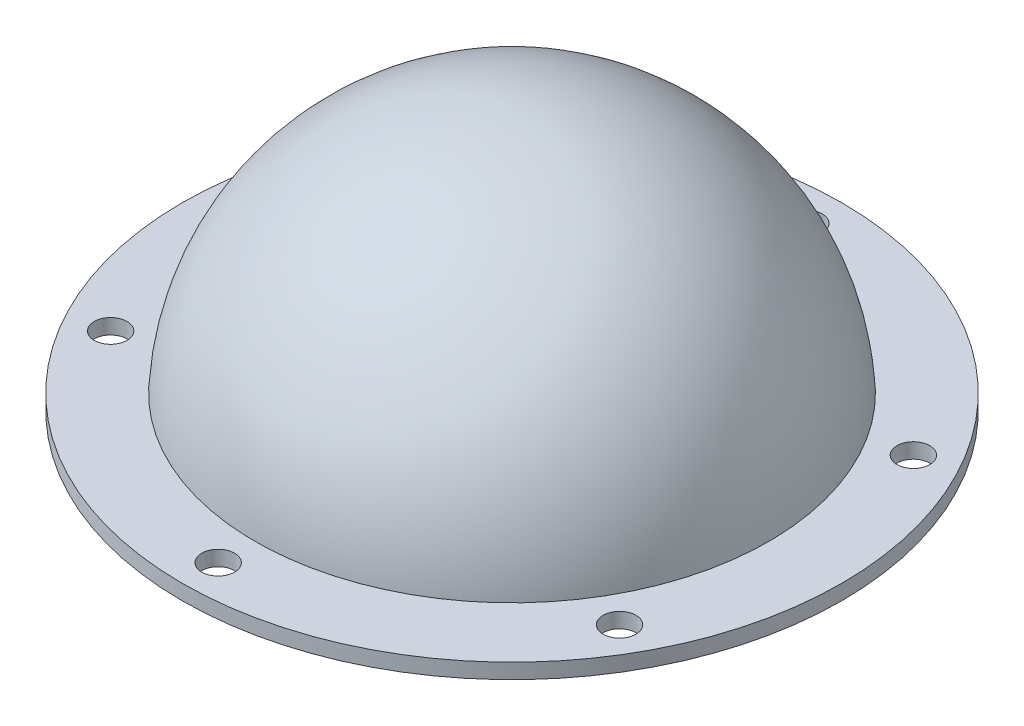
SolidWorks part; units mm, degrees
ref_plane "Front Plane" through (0, 0, 0) normal (0, 0, 1) x (1, 0, 0)
ref_plane "Top Plane" through (0, 0, 0) normal (0, 1, 0) x (1, 0, 0)
ref_plane "Right Plane" through (0, 0, 0) normal (1, 0, 0) x (0, 0, -1)
sketch "Sketch1" plane through (0, 0, 0) normal (1, 0, 0) x (0, 0, -1)
  line L0 (31.75, 0) -> (-31.75, 0) construction
  line L1 (-31.75, 0) -> (-43.201, 0)
  line L2 (-43.201, 0) -> (-43.201, 1.9844)
  line L3 (-43.201, 1.9844) -> (-33.676, 1.9844)
  line L4 (0, -1000) -> (0, 49000) construction
  line L5 (0, 33.7344) -> (0, 31.75)
  arc A0 (-31.75, 0) -> (0, 31.75) centre (0, 0) cw
  arc A1 (-33.676, 1.9844) -> (0, 33.7344) centre (0, 0) cw
  arc A2 (-33.7344, 0) -> (33.7344, 0) centre (0, 0) cw construction
  arc A3 (-31.75, 0) -> (31.75, 0) centre (0, 0) cw construction
  point P4 (0, 0)
  dimension "D1" = 63.5
  dimension "D3" = 9.525
  dimension "D4" = 1.9844
  dimension "D2" = 1.9844
revolve "Revolve1" add sketch "Sketch1" angle 360 about L4
sketch "Sketch2" plane through (0, 1.9844, 0) normal (0, 1, 0) x (1, 0, 0)
  line L0 (0, -38.5) -> (0, 38.5) construction
  line L1 (0, 38.5) -> (-33.342, 19.25) construction
  line L2 (-33.342, 19.25) -> (-33.342, -19.25) construction
  line L3 (-33.342, -19.25) -> (0, -38.5) construction
  line L4 (0, -38.5) -> (33.342, -19.25) construction
  line L5 (33.342, -19.25) -> (33.342, 19.25) construction
  line L6 (33.342, 19.25) -> (0, 38.5) construction
  circle A0 centre (0, 0) radius 33.342 construction
  circle A1 centre (0, -38.5) radius 2.15
  circle A2 centre (-33.342, -19.25) radius 2.15
  circle A3 centre (-33.342, 19.25) radius 2.15
  circle A4 centre (0, 38.5) radius 2.15
  circle A5 centre (33.342, 19.25) radius 2.15
  circle A6 centre (33.342, -19.25) radius 2.15
  point P21 (0, 0)
  dimension "D2" = 4.3
  dimension "D1" = 77
extrude "Cut-Extrude1" cut sketch "Sketch2" against normal blind 10
equation "\"D4@Sketch1\"=\"D2@Sketch1\""
